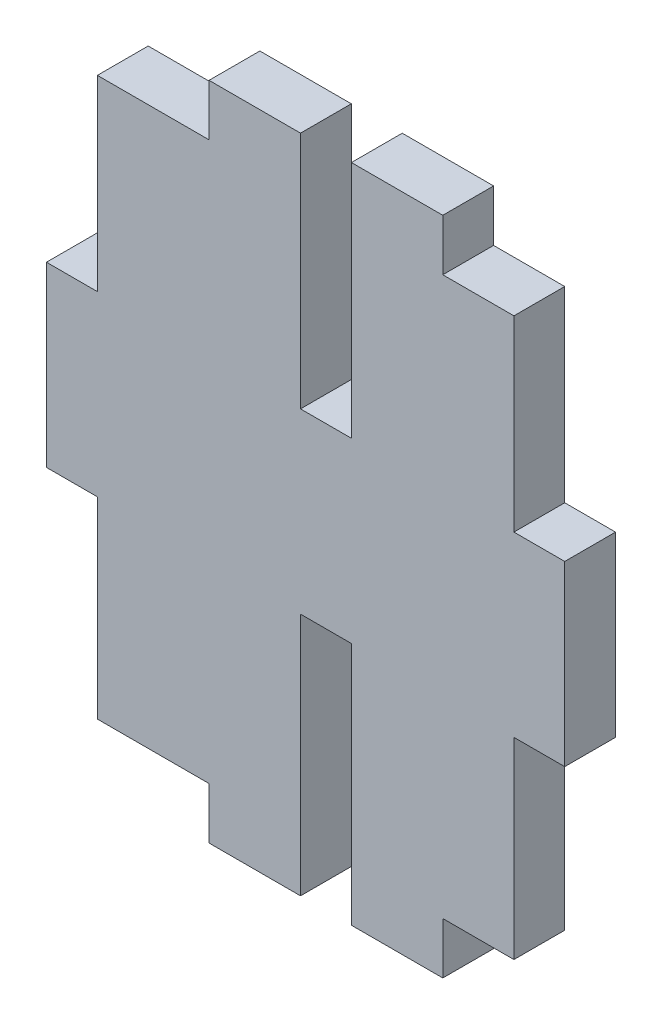
SolidWorks part; units mm, degrees
material "Acrylique (impact moyen-haut)"
ref_plane "Plan de face" through (0, 0, 0) normal (0, 0, 1) x (1, 0, 0)
ref_plane "Plan de dessus" through (0, 0, 0) normal (0, 1, 0) x (1, 0, 0)
ref_plane "Plan de droite" through (0, 0, 0) normal (1, 0, 0) x (0, 0, -1)
sketch "Esquisse1" plane through (0, 0, 0) normal (0, 0, 1) x (1, 0, 0)
  line L1 (25.5, -32.5) -> (-25.5, -32.5)
  line L2 (25.5, -32.5) -> (25.5, 32.5)
  line L3 (25.5, 32.5) -> (-25.5, 32.5)
  line L4 (-25.5, -32.5) -> (-25.5, 32.5)
  line L5 (25.5, -32.5) -> (-25.5, 32.5) construction
  line L6 (25.5, 32.5) -> (-25.5, -32.5) construction
  point P0 (0, 0)
  dimension "D1" = 51
  dimension "D2" = 65
extrude "Boss.-Extru.1" add sketch "Esquisse1" along normal blind 5
sketch "Esquisse2" plane through (0, 0, 5) normal (0, 0, 1) x (1, 0, 0)
  line L0 (-25.5, 32.5) -> (-25.5, -32.5) construction
  line L1 (25.5, 32.5) -> (-25.5, 32.5) construction
  line L2 (-25.5, -32.5) -> (25.5, -32.5) construction
  line L3 (-25.5, 9) -> (-20.49, 9)
  line L4 (-25.5, 9) -> (-25.5, 32.5)
  line L5 (-25.5, 32.5) -> (-20.49, 32.5)
  line L6 (-20.49, 9) -> (-20.49, 32.5)
  line L7 (-25.5, -8.49) -> (-20.49, -8.49)
  line L8 (-25.5, -8.49) -> (-25.5, -32.5)
  line L9 (-25.5, -32.5) -> (-20.49, -32.5)
  line L10 (-20.49, -8.49) -> (-20.49, -32.5)
  line L11 (-0.5, 32.5) -> (-0.5, -43.3751) construction
  line L12 (25.5, -32.5) -> (25.5, 32.5) construction
  line L13 (-0.5, 32.5) -> (4.51, 32.5)
  line L14 (-0.5, 32.5) -> (-0.5, 9)
  line L15 (-0.5, 9) -> (4.51, 9)
  line L16 (4.51, 32.5) -> (4.51, 9)
  line L17 (-0.5, -8.49) -> (4.51, -8.49)
  line L18 (-0.5, -8.49) -> (-0.5, -32.5)
  line L19 (-0.5, -32.5) -> (4.51, -32.5)
  line L20 (4.51, -8.49) -> (4.51, -32.5)
  line L21 (20.5, 32.5) -> (25.5, 32.5)
  line L22 (20.5, 32.5) -> (20.5, 9)
  line L23 (20.5, 9) -> (25.5, 9)
  line L24 (25.5, 32.5) -> (25.5, 9)
  line L26 (25.5, -32.5) -> (25.5, -8.49)
  line L27 (20.5, -8.49) -> (25.5, -8.49)
  line L28 (20.5, -32.5) -> (20.5, -8.49)
  line L29 (20.5, -32.5) -> (25.5, -32.5)
  point P0 (-25.5, 9)
  point P5 (-25.5, -8.49)
  point P16 (-0.5, 32.5)
  point P19 (20.5, 32.5)
  point P21 (-0.5, 8.6359)
  point P25 (-0.5, -8.49)
  dimension "D1" = 23.5
  dimension "D2" = 17.49
  dimension "D3" = 5.01
  dimension "D4" = 5.01
  dimension "D5" = 25
  dimension "D6" = 25
  dimension "D7" = 5.01
  dimension "D8" = 23.5
  dimension "D9" = 5.01
  dimension "D10" = 17.49
  dimension "D11" = 46
  dimension "D12" = 24.01
  dimension "D13" = 17.49
  dimension "D14" = 24.01
  dimension "D15" = 46
  dimension "D16" = 5
  dimension "D17" = 65
  dimension "D18" = 5
  dimension "D19" = 24.01
extrude "Enlèv. mat.-Extru.1" cut sketch "Esquisse2" against normal blind 5
sketch "Esquisse3" plane through (0, 0, 5) normal (0, 0, 1) x (1, 0, 0)
  line L0 (-25.5, 6.3919) -> (-25.5, 42.9479) construction
  line L1 (25.5, 3.4923) -> (25.5, 35.0047) construction
  line L2 (-9.5, 32.5) -> (-25.5, 32.5)
  line L3 (-0.5, 32.5) -> (-20.49, 32.5) construction
  line L4 (-25.5, 9) -> (-25.5, -8.49) construction
  line L6 (-9.5, 32.5) -> (-9.5, 27.43)
  line L7 (-9.5, 27.43) -> (-25.5, 27.43)
  line L8 (-25.5, 32.5) -> (-25.5, 27.43)
  line L9 (25.5, -8.49) -> (25.5, 9) construction
  line L10 (0, 0) -> (-31.5587, 0) construction
  line L11 (13.5, 32.5) -> (25.5, 32.5)
  line L12 (13.5, 32.5) -> (13.5, 27.43)
  line L13 (13.5, 27.43) -> (25.5, 27.43)
  line L14 (25.5, 32.5) -> (25.5, 27.43)
  line L15 (25.5, -32.5) -> (25.5, -27.43)
  line L16 (13.5, -27.43) -> (25.5, -27.43)
  line L17 (13.5, -32.5) -> (13.5, -27.43)
  line L18 (13.5, -32.5) -> (25.5, -32.5)
  line L19 (-25.5, -32.5) -> (-25.5, -27.43)
  line L20 (-9.5, -27.43) -> (-25.5, -27.43)
  line L21 (-9.5, -32.5) -> (-9.5, -27.43)
  line L22 (-9.5, -32.5) -> (-25.5, -32.5)
  point P0 (-9.5, 32.5)
  dimension "D1" = 16
  dimension "D2" = 12
  dimension "D3" = 5.07
  dimension "D4" = 5.07
  dimension "D5" = 23
extrude "Enlèv. mat.-Extru.2" cut sketch "Esquisse3" against normal blind 5
